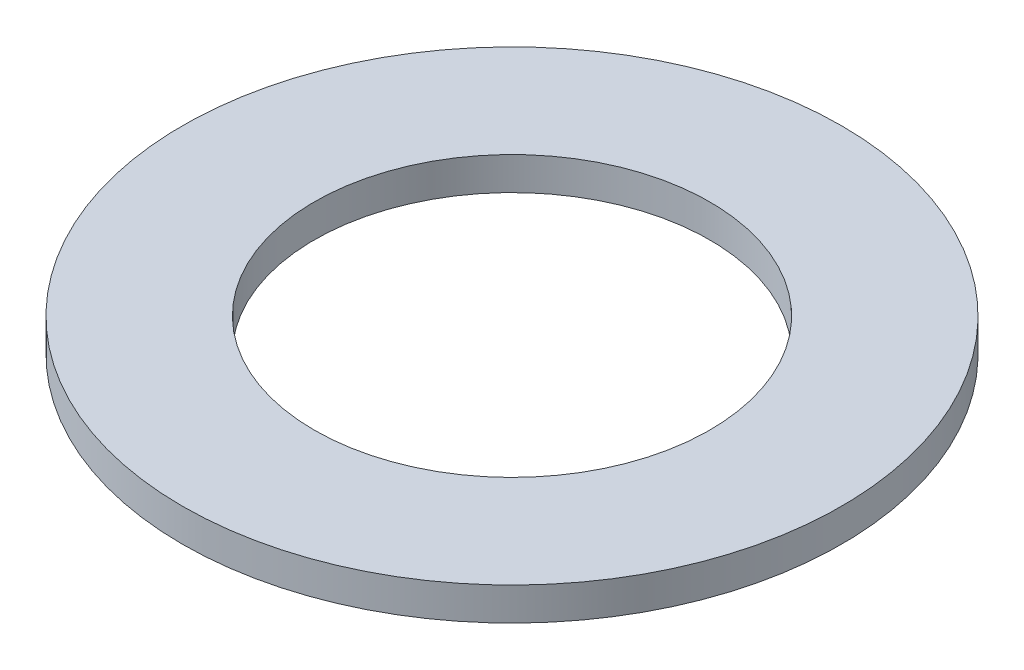
SolidWorks part; units mm, degrees
ref_plane "Front Plane" through (0, 0, 0) normal (0, 0, 1) x (1, 0, 0)
ref_plane "Top Plane" through (0, 0, 0) normal (0, 1, 0) x (1, 0, 0)
ref_plane "Right Plane" through (0, 0, 0) normal (1, 0, 0) x (0, 0, -1)
sketch "Sketch1" plane through (0, 0, 0) normal (0, 1, 0) x (1, 0, 0)
  circle A0 centre (0, 0) radius 31.75
  circle A1 centre (0, 0) radius 19.05
  dimension "D1" = 38.1
  dimension "D2" = 63.5
extrude "Boss-Extrude1" add sketch "Sketch1" along normal blind 3.175
